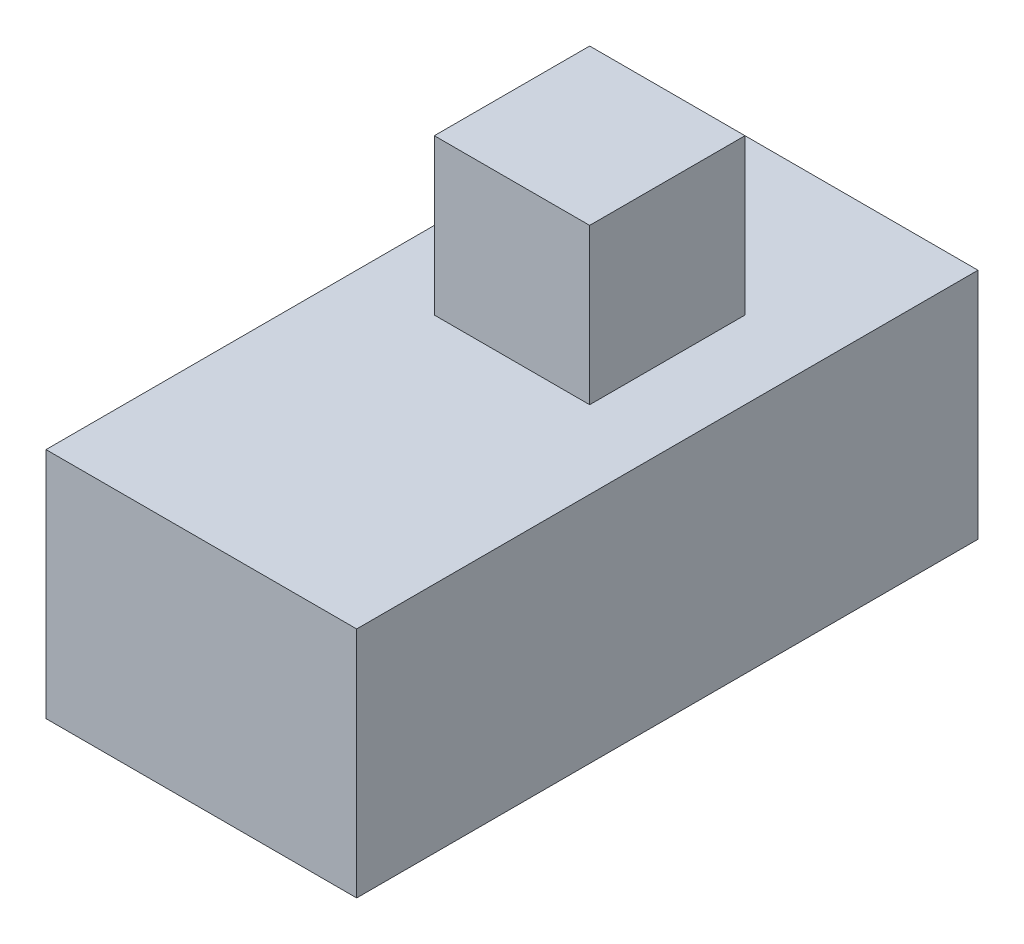
SolidWorks part; units mm, degrees
ref_plane "Front Plane" through (0, 0, 0) normal (0, 0, 1) x (1, 0, 0)
ref_plane "Top Plane" through (0, 0, 0) normal (0, 1, 0) x (1, 0, 0)
ref_plane "Right Plane" through (0, 0, 0) normal (1, 0, 0) x (0, 0, -1)
sketch "Sketch1" plane through (0, 0, 0) normal (0, 1, 0) x (1, 0, 0)
  line L1 (0, 0) -> (4, 0)
  line L2 (0, 0) -> (0, -8)
  line L3 (0, -8) -> (4, -8)
  line L4 (4, 0) -> (4, -8)
  dimension "D1" = 8
  dimension "D2" = 4
extrude "Boss-Extrude1" add sketch "Sketch1" along normal blind 3
sketch "Sketch3" plane through (0, 3, 0) normal (0, 1, 0) x (1, 0, 0)
  line L0 (0, -2) -> (4, -2) construction
  line L1 (1, -2) -> (3, -2)
  line L2 (1, -2) -> (1, -4)
  line L3 (1, -4) -> (3, -4)
  line L4 (3, -2) -> (3, -4)
  line L5 (0, 0) -> (0, -8) construction
  line L6 (4, -8) -> (4, 0) construction
  line L7 (4, -2) -> (2, -2) construction
  line L8 (4, 0) -> (0, 0) construction
  point P10 (2, -2)
  dimension "D1" = 2
  dimension "D2" = 2
  dimension "D3" = 2
extrude "Boss-Extrude2" add sketch "Sketch3" along normal blind 2
